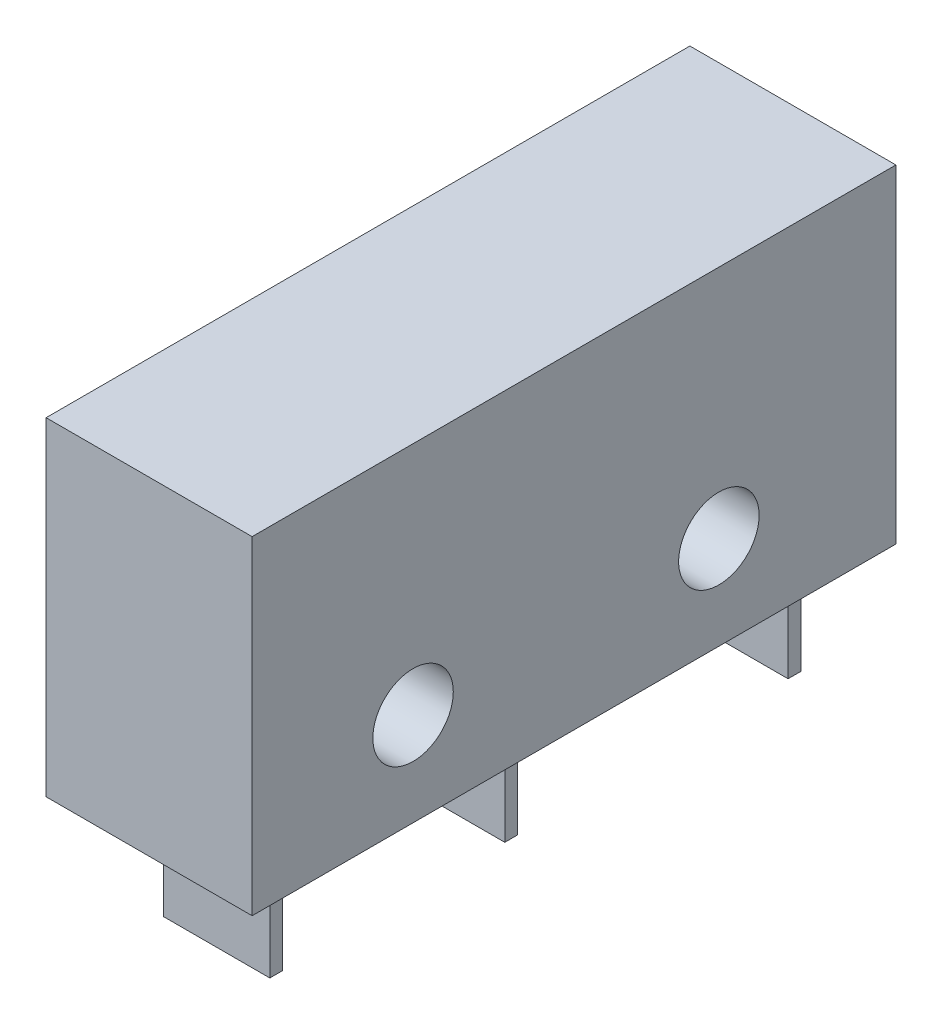
SolidWorks part; units mm, degrees
ref_plane "Front Plane" through (0, 0, 0) normal (0, 0, 1) x (1, 0, 0)
ref_plane "Top Plane" through (0, 0, 0) normal (0, 1, 0) x (1, 0, 0)
ref_plane "Right Plane" through (0, 0, 0) normal (1, 0, 0) x (0, 0, -1)
sketch "Sketch1" plane through (0, 0, 0) normal (1, 0, 0) x (0, 0, -1)
  line L1 (-10, -5.1) -> (10, -5.1)
  line L2 (-10, -5.1) -> (-10, 5.1)
  line L3 (-10, 5.1) -> (10, 5.1)
  line L4 (10, -5.1) -> (10, 5.1)
  line L5 (-10, -5.1) -> (10, 5.1) construction
  line L6 (-10, 5.1) -> (10, -5.1) construction
  point P0 (0, 0)
  dimension "D1" = 10.2
  dimension "D2" = 20
extrude "Boss-Extrude1" add sketch "Sketch1" along normal mid plane 6.4
sketch "Sketch2" plane through (0, 0, 0) normal (1, 0, 0) x (0, 0, -1)
  line L0 (-10, -5.1) -> (10, -5.1) construction
  line L1 (-10, 5.1) -> (-10, -5.1) construction
  line L2 (-5, -2.2) -> (4.5, -2.2) construction
  circle A0 centre (-5, -2.2) radius 1.25
  circle A1 centre (4.5, -2.2) radius 1.25
  dimension "D1" = 2.5
  dimension "D2" = 2.9
  dimension "D4" = 9.5
  dimension "D3" = 14.5
extrude "Cut-Extrude1" cut sketch "Sketch2" against normal through all both and the other way through all
sketch "Sketch3" plane through (0, -5.1, 0) normal (0, -1, 0) x (1, 0, 0)
  line L0 (0, -10) -> (0, 10) construction
  line L1 (-1.65, -8.6) -> (1.65, -8.6)
  line L2 (-1.65, -8.6) -> (-1.65, -8.2)
  line L3 (-1.65, -8.2) -> (1.65, -8.2)
  line L4 (1.65, -8.6) -> (1.65, -8.2)
  line L5 (-1.65, -8.6) -> (1.65, -8.2) construction
  line L6 (-1.65, -8.2) -> (1.65, -8.6) construction
  line L7 (-1.65, 0.2) -> (1.65, 0.2)
  line L8 (-1.65, 0.2) -> (-1.65, 0.6)
  line L9 (-1.65, 0.6) -> (1.65, 0.6)
  line L10 (1.65, 0.2) -> (1.65, 0.6)
  line L11 (-1.65, 0.2) -> (1.65, 0.6) construction
  line L12 (-1.65, 0.6) -> (1.65, 0.2) construction
  line L13 (-1.65, 7.5) -> (1.65, 7.5)
  line L14 (-1.65, 7.5) -> (-1.65, 7.9)
  line L15 (-1.65, 7.9) -> (1.65, 7.9)
  line L16 (1.65, 7.5) -> (1.65, 7.9)
  line L17 (-1.65, 7.5) -> (1.65, 7.9) construction
  line L18 (-1.65, 7.9) -> (1.65, 7.5) construction
  line L19 (3.2, -10) -> (-3.2, -10) construction
  line L20 (3.2, 10) -> (-3.2, 10) construction
  line L21 (3.2, -10) -> (-3.2, -10) construction
  line L22 (1.65, 7.9) -> (1.65, -8.6) construction
  point P0 (0, -8.4)
  point P5 (0, 0.4)
  point P10 (0, 7.7)
  point P20 (1.65, -9.1451)
  dimension "D1" = 1.6
  dimension "D2" = 8.8
  dimension "D3" = 7.3
  dimension "D4" = 3.3
  dimension "D5" = 0.4
extrude "Boss-Extrude2" add sketch "Sketch3" along normal blind 3.5
